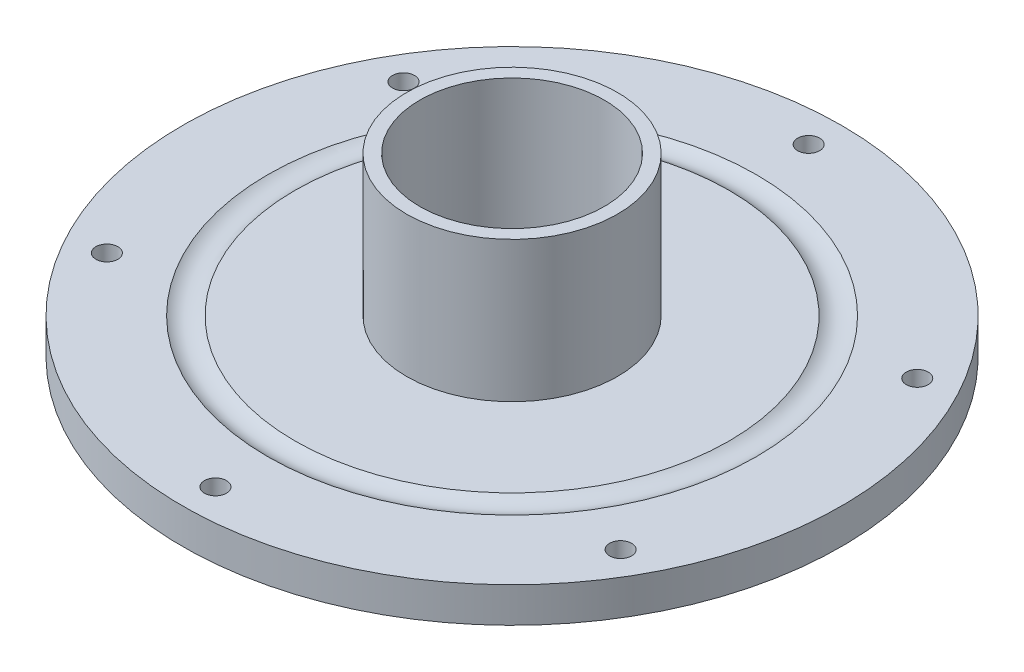
SolidWorks part; units mm, degrees
material "PA Type 6"
ref_plane "Front Plane" through (0, 0, 0) normal (0, 0, 1) x (1, 0, 0)
ref_plane "Top Plane" through (0, 0, 0) normal (0, 1, 0) x (1, 0, 0)
ref_plane "Right Plane" through (0, 0, 0) normal (1, 0, 0) x (0, 0, -1)
ref_plane "Plane1" through (0, 0, 0) normal (0, 0, -1) x (-1, 0, 0)
sketch "Sketch1" plane through (0, 0, 0) normal (0, 0, -1) x (-1, 0, 0)
  line L0 (-59, -1.1276) -> (-47, -1.1276)
  line L1 (-46, -0.1276) -> (-46, 5.8724)
  line L2 (-46, 5.8724) -> (-47, 6.8724)
  line L3 (-47, 6.8724) -> (-49.4043, 6.8724)
  line L4 (-55.5957, 6.8724) -> (-59, 6.8724)
  line L5 (-59, 6.8724) -> (-60, 5.8724)
  line L6 (-60, 5.8724) -> (-60, -0.1276)
  line L7 (0, 0) -> (0, 6.8724) construction
  arc A0 (-47, -1.1276) -> (-46, -0.1276) centre (-47, -0.1276) ccw
  arc A1 (-49.4043, 6.8724) -> (-55.5957, 6.8724) centre (-52.5, 11) cw
  arc A2 (-60, -0.1276) -> (-59, -1.1276) centre (-59, -0.1276) ccw
  dimension "D1" = 5.1595
  dimension "D2" = 14
  dimension "D3" = 6.1914
  dimension "D4" = 8
revolve "Revolve1" add sketch "Sketch1" angle 360 about L7
sketch "Sketch2" plane through (0, -1.1276, 0) normal (0, -1, 0) x (1, 0, 0)
  circle A0 centre (0, 0) radius 75
  circle M1 centre (0, 0) radius 47
  circle M2 centre (0, 0) radius 59
  dimension "D1" = 150
extrude "Boss-Extrude1" add sketch "Sketch2" against normal blind 8 contours A0 M2 | M1
sketch "Sketch4" plane through (0, -1.1276, 0) normal (0, -1, 0) x (1, 0, 0)
  circle A0 centre (0, 0) radius 2.5
extrude "Cut-Extrude1" cut sketch "Sketch4" against normal blind 8
sketch "Sketch5" plane through (0, -1.1276, 0) normal (0, -1, 0) x (1, 0, 0)
  circle A4 centre (0, 0) radius 17.5 construction
  circle A5 centre (0, 0) radius 21 construction
  circle A6 centre (0, 17.5) radius 1.9
  circle A7 centre (17.5, 0) radius 1.9
  circle A8 centre (0, -17.5) radius 1.9
  circle A9 centre (-17.5, 0) radius 1.9
  point P12 (-6.9839, -2.8428)
  point P16 (0, 0)
  dimension "D1" = 3.8
  dimension "D2" = 4
  dimension "D4" = 42
  dimension "D5" = 35
extrude "Cut-Extrude2" cut sketch "Sketch5" against normal blind 8
sketch "Sketch7" plane through (0, -1.1276, 0) normal (0, -1, 0) x (1, 0, 0)
  circle A1 centre (0, 0) radius 22.5
  dimension "D1" = 45
extrude "Cut-Extrude3" cut sketch "Sketch7" against normal blind 3
sketch "Sketch8" plane through (0, 6.8724, 0) normal (0, 1, 0) x (1, 0, 0)
  circle A0 centre (0, 0) radius 24
  circle A1 centre (0, 0) radius 21
  dimension "D1" = 48
  dimension "D2" = 3
extrude "Boss-Extrude3" add sketch "Sketch8" along normal blind 32
sketch "Sketch9" plane through (0, -1.1276, 0) normal (0, -1, 0) x (1, 0, 0)
  circle A0 centre (0, 0) radius 67.5 construction
  circle A1 centre (0, -67.5) radius 2.5
  circle A2 centre (-58.4567, -33.75) radius 2.5
  circle A3 centre (-58.4567, 33.75) radius 2.5
  circle A4 centre (0, 67.5) radius 2.5
  circle A5 centre (58.4567, 33.75) radius 2.5
  circle A6 centre (58.4567, -33.75) radius 2.5
  point P17 (0, 0)
  dimension "D1" = 6
  dimension "D2" = 135
  dimension "D3" = 5
extrude "Cut-Extrude4" cut sketch "Sketch9" against normal blind 8
sketch "Sketch10" plane through (0, -1.1276, 0) normal (0, -1, 0) x (1, 0, 0)
  circle A2 centre (-15.1005, 42.8809) radius 2
  circle A3 centre (21.1606, 39.7452) radius 2
  circle A4 centre (-40.951, 20.1763) radius 2
  circle A5 centre (-42.2195, -16.198) radius 2
extrude "Cut-Extrude7" cut sketch "Sketch10" against normal blind 2
